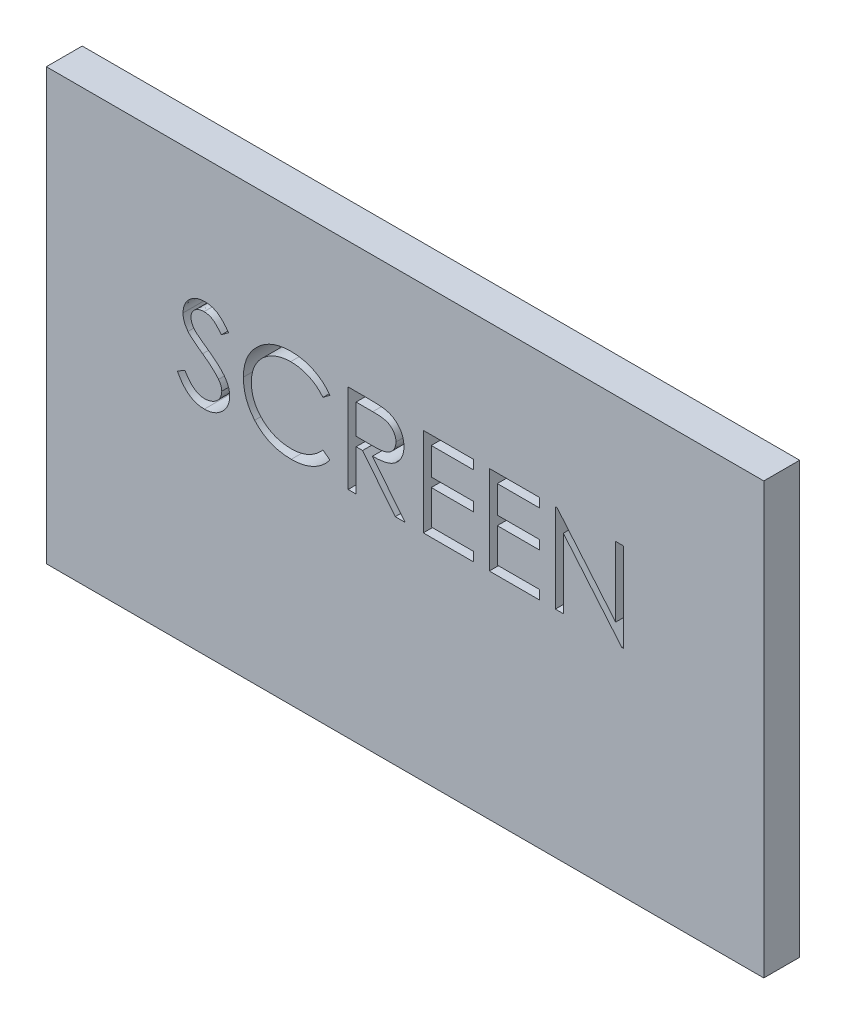
SolidWorks part; units mm, degrees
ref_plane "Front Plane" through (0, 0, 0) normal (0, 0, 1) x (1, 0, 0)
ref_plane "Top Plane" through (0, 0, 0) normal (0, 1, 0) x (1, 0, 0)
ref_plane "Right Plane" through (0, 0, 0) normal (1, 0, 0) x (0, 0, -1)
sketch "Sketch1" plane through (0, 0, 0) normal (0, 0, 1) x (1, 0, 0)
  line L1 (-121.7916, 98.9404) -> (30.6084, 98.9404)
  line L2 (-121.7916, 98.9404) -> (-121.7916, 7.5004)
  line L3 (-121.7916, 7.5004) -> (30.6084, 7.5004)
  line L4 (30.6084, 98.9404) -> (30.6084, 7.5004)
  dimension "D1" = 152.4
  dimension "D2" = 91.44
extrude "Boss-Extrude1" add sketch "Sketch1" along normal blind 7.62
sketch "Sketch2" plane through (0, 0, 7.62) normal (0, 0, 1) x (1, 0, 0)
  line L0 (-121.7916, 53.2204) -> (30.6084, 53.2204) construction
  line L1 (-121.7916, 98.9404) -> (-121.7916, 7.5004) construction
  line L2 (30.6084, 7.5004) -> (30.6084, 98.9404) construction
  text T0 "SCREEN" font "Century Gothic" height in points 72
extrude "Cut-Extrude1" cut sketch "Sketch2" against normal through all
